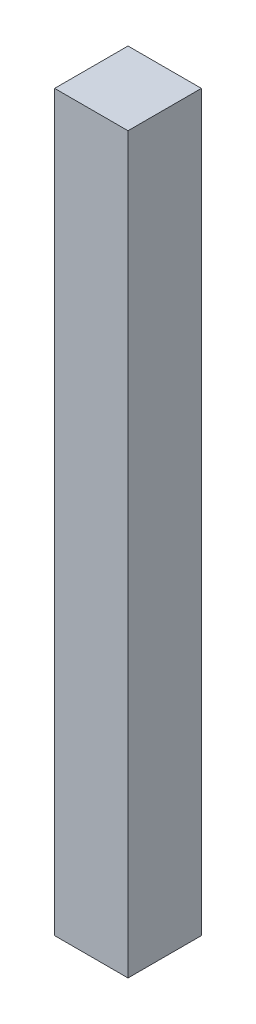
SolidWorks part; units mm, degrees
ref_plane "Front Plane" through (0, 0, 0) normal (0, 0, 1) x (1, 0, 0)
ref_plane "Top Plane" through (0, 0, 0) normal (0, 1, 0) x (1, 0, 0)
ref_plane "Right Plane" through (0, 0, 0) normal (1, 0, 0) x (0, 0, -1)
sketch "Sketch1" plane through (0, 0, 0) normal (0, 0, 1) x (1, 0, 0)
  line L1 (0, 0) -> (20, 0)
  line L2 (0, 0) -> (0, 200)
  line L3 (0, 200) -> (20, 200)
  line L4 (20, 0) -> (20, 200)
  dimension "D1" = 200
  dimension "D2" = 20
extrude "Boss-Extrude1" add sketch "Sketch1" along normal blind 20
